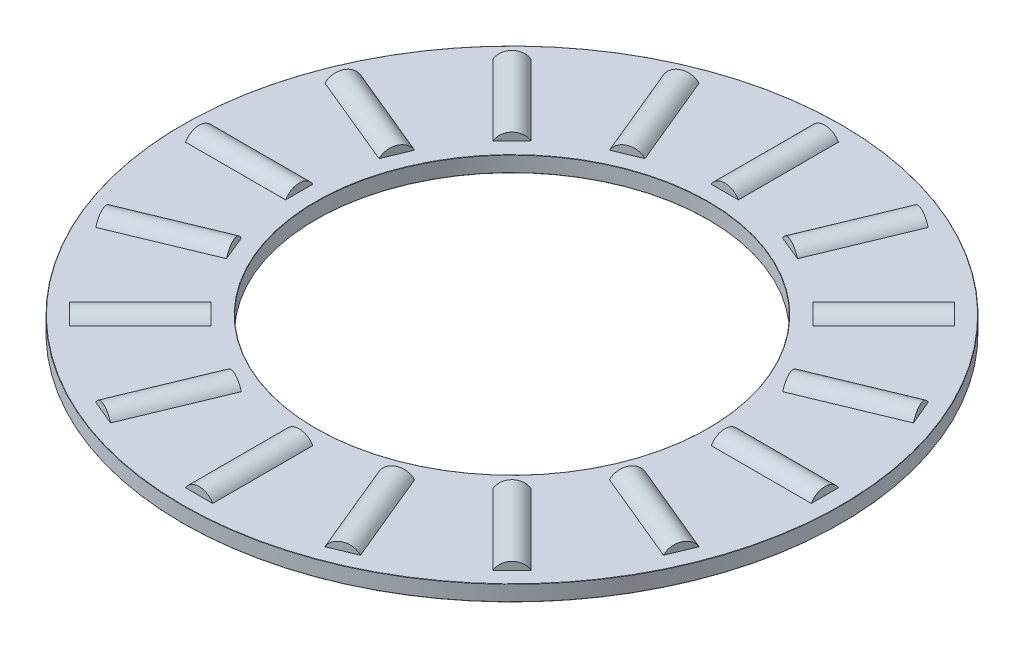
SolidWorks part; units mm, degrees
ref_plane "Front Plane" through (0, 0, 0) normal (0, 0, 1) x (1, 0, 0)
ref_plane "Top Plane" through (0, 0, 0) normal (0, 1, 0) x (1, 0, 0)
ref_plane "Right Plane" through (0, 0, 0) normal (1, 0, 0) x (0, 0, -1)
sketch "Sketch1" plane through (0, 0, 0) normal (1, 0, 0) x (0, 0, -1)
  line L0 (-21, 0) -> (21, 0) construction
  line L1 (0, -1) -> (0, 1) construction
  line L2 (-21, 0.5) -> (-12.5, 0.5)
  line L3 (-21, 0.5) -> (-21, -0.5)
  line L4 (-21, -0.5) -> (-12.5, -0.5)
  line L5 (-12.5, 0.5) -> (-12.5, -0.5)
  line L7 (-16.75, 1) -> (-16.75, 0.5) construction
  line L8 (-19.9375, 1) -> (-13.5625, 1) construction
  line L9 (-19.9375, 1) -> (-19.9375, -1) construction
  line L10 (-19.9375, -1) -> (-13.5625, -1) construction
  line L11 (-13.5625, 1) -> (-13.5625, -1) construction
  point P16 (-19.9375, 0)
  dimension "D1" = 6.375
  dimension "OD" = 42
  dimension "Shaft Dia" = 25
  dimension "Th" = 2
  dimension "D2" = 1
  dimension "D3" = 8.5
revolve "Revolve1" add sketch "Sketch1" angle 360 about L1
sketch "Sketch3" plane through (0, 0, 0) normal (1, 0, 0) x (0, 0, -1)
  line L0 (-19.9375, 1) -> (-19.9375, -1) construction
  line L1 (-19.9375, 0) -> (-13.5625, 0)
  line L2 (-19.9375, 0) -> (-19.9375, 1)
  line L3 (-19.9375, 1) -> (-13.5625, 1)
  line L4 (-13.5625, 0) -> (-13.5625, 1)
revolve "Cut-Revolve1" cut sketch "Sketch3" angle 360 about L1
sketch "Sketch2" plane through (0, 0, 0) normal (1, 0, 0) x (0, 0, -1)
  line L1 (-19.9375, 0) -> (-13.5625, 0)
  line L2 (-19.9375, 0) -> (-19.9375, 1)
  line L3 (-19.9375, 1) -> (-13.5625, 1)
  line L4 (-13.5625, 0) -> (-13.5625, 1)
revolve "Revolve2" add sketch "Sketch2" angle 360 about L1
ref_axis "Axis1" through (0, 1, 0) along (0, -1, 0)
pattern_circular "CirPattern1" count 16 every 22.5 about axis through (0, 1, 0) along (0, -1, 0) of bodies 187 411
pattern_circular "CirPattern2" count 16 every 22.5 about axis through (0, 0, 0) along (0, 1, 0) of "Cut-Revolve1"
sketch "Sketch4" plane through (0, 0, 0) normal (1, 0, 0) x (0, 0, -1)
  line L0 (-21, 0.5) -> (-21, -0.5) construction
  line L1 (-21, 9) -> (-12.5, 9)
  line L2 (-21, 9) -> (-21, 10)
  line L3 (-21, 10) -> (-12.5, 10)
  line L4 (-12.5, 9) -> (-12.5, 10)
  line L5 (-21, -10) -> (-12.5, -10)
  line L6 (-21, -10) -> (-21, -9)
  line L7 (-21, -9) -> (-12.5, -9)
  line L8 (-12.5, -10) -> (-12.5, -9)
  line L10 (-12.5, 0.5) -> (-12.5, -0.5) construction
  line L11 (0, 0) -> (-21, 0) construction
  line L12 (-21, 0) -> (21, 0) construction
  line L13 (0, -1) -> (0, 1) construction
  dimension "Ht" = 20
  dimension "Washer Th" = 1
  dimension "Washer ID" = 25
  dimension "Washer OD" = 42
revolve "Revolve3" [suppressed] add sketch "Sketch4" angle 360 about L1
fillet "Fillet1" [suppressed] radius 0.02
fillet "Fillet2" radius 0.02 4 edges at (0, -0.5, -12.5) (0, 0.5, -12.5) (0, -0.5, -21) (0, 0.5, -21)
fillet "Fillet3" [suppressed] radius 0.02
equation "\"D2@Sketch1\" = \"Th@Sketch1\"*.5"
equation "\"D1@Fillet1\" = \"Th@Sketch1\"*.01"
equation "\"D1@Fillet2\" = \"D1@Fillet1\""
equation "\"D1@Fillet3\" = \"D1@Fillet1\""
equation "\"D1@Sketch1\" = \"D3@Sketch1\"*.75"
equation "\"Angle@CirPattern1\" = 360/\"Rollers@CirPattern1\""
equation "\"Rollers@CirPattern1\" = \"OD@Sketch1\"*.375"
equation "\"D1@CirPattern2\" = \"Rollers@CirPattern1\""
equation "\"D2@CirPattern2\" = \"Angle@CirPattern1\""
equation "\"Ht@Sketch4\" = \"Th@Sketch1\"*10"
